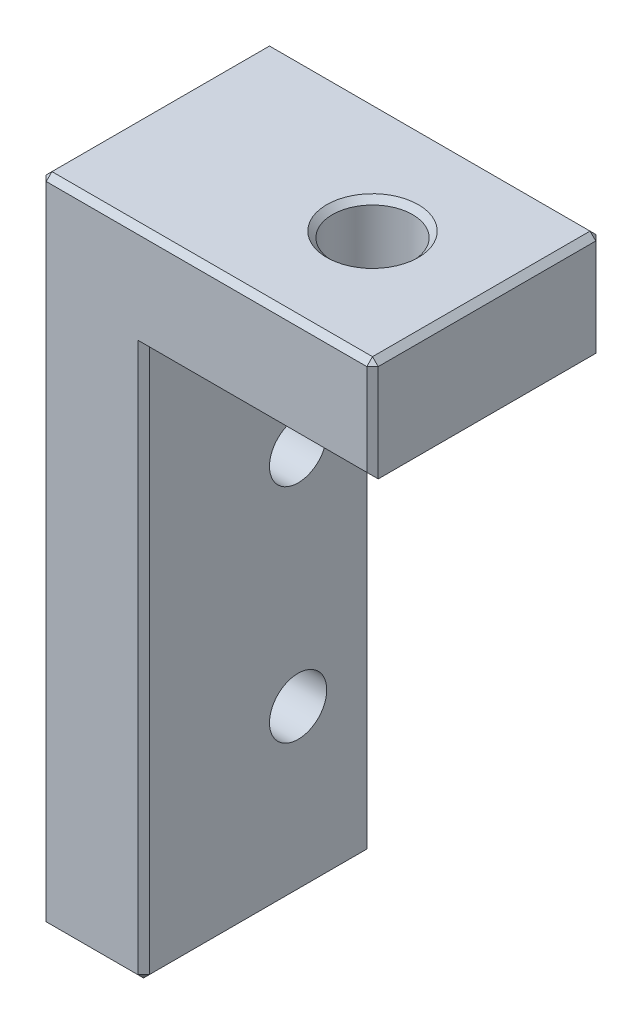
SolidWorks part; units mm, degrees
ref_plane "Front Plane" through (0, 0, 0) normal (0, 0, 1) x (1, 0, 0)
ref_plane "Top Plane" through (0, 0, 0) normal (0, 1, 0) x (1, 0, 0)
ref_plane "Right Plane" through (0, 0, 0) normal (1, 0, 0) x (0, 0, -1)
sketch "Sketch1" plane through (0, 0, 0) normal (0, 0, 1) x (1, 0, 0)
  line L0 (0, 39.5625) -> (0, -32.0625) construction
  line L1 (-37.375, 0) -> (58.375, 0) construction
  line L2 (0, 0) -> (0, 28.5)
  line L3 (0, 28.5) -> (14.5, 28.5)
  line L4 (14.5, 28.5) -> (14.5, 24)
  line L5 (14.5, 24) -> (4.5, 24)
  line L6 (4.5, 24) -> (4.5, 0)
  line L7 (4.5, 0) -> (0, 0)
  dimension "D1" = 4.5
  dimension "D2" = 4.5
  dimension "D3" = 10
  dimension "D4" = 24
extrude "Boss-Extrude1" add sketch "Sketch1" along normal blind 10
sketch "Sketch2" plane through (0, 24, 0) normal (0, -1, 0) x (1, 0, 0)
  circle A0 centre (9.5, 5) radius 1.75
  dimension "D1" = 3.5
  dimension "D3" = 9.5
  dimension "D2" = 5
extrude "Cut-Extrude1" cut sketch "Sketch2" against normal blind 10
sketch "Sketch3" plane through (4.5, 0, 0) normal (1, 0, 0) x (0, 0, -1)
  line L0 (-5, 31.8711) -> (-5, -3.4018) construction
  line L1 (-21.2213, 12) -> (22.3467, 12) construction
  line L2 (0, 0) -> (0, 24) construction
  circle A0 centre (-3.25, 7.15) radius 1.25
  circle A1 centre (-3.25, 16.85) radius 1.25
  dimension "D3" = 2.5
  dimension "D5" = 3.25
  dimension "D1" = 5
  dimension "D2" = 12
  dimension "D4" = 4.85
extrude "Cut-Extrude2" cut sketch "Sketch3" against normal blind 10
chamfer "Chamfer1" distance 0.25 20 edges at (9.5, 28.5, 3.25) (0, 0, 5) (4.5, 0, 5) (0, 14.25, 10) (2.25, 0, 10) (4.5, 12, 10) (9.5, 24, 10) (14.5, 26.25, 10) (14.5, 28.5, 5) (7.25, 28.5, 10) (0, 28.5, 5) (4.5, 12, 0) (9.5, 24, 0) (14.5, 26.25, 0) (7.25, 28.5, 0) (0, 14.25, 0) (2.25, 0, 0) (11.25, 24, 5) (0, 8.4, 3.25) (0, 18.1, 3.25)
